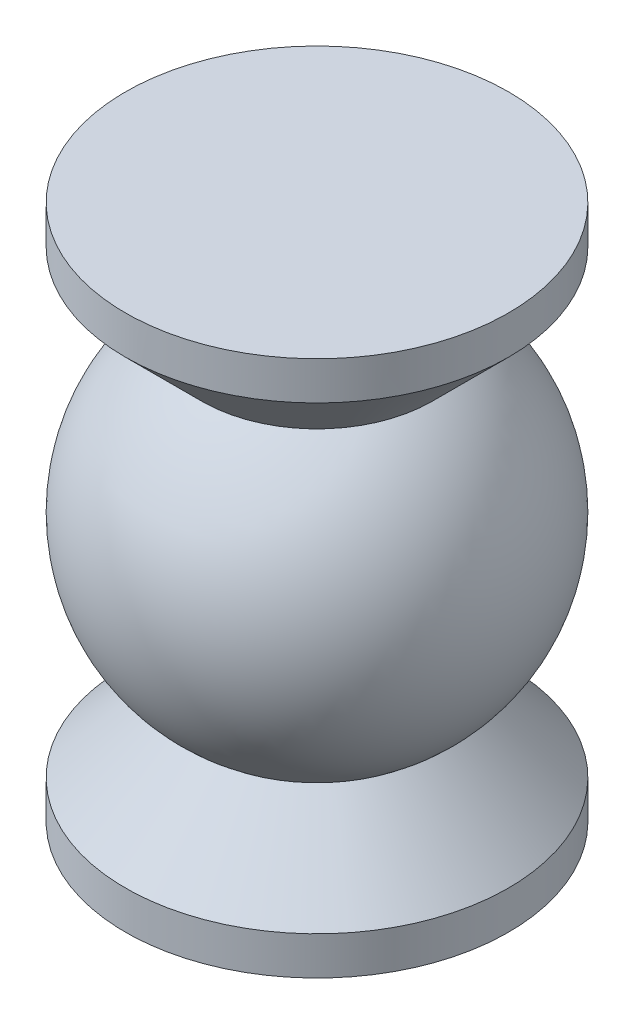
SolidWorks part; units mm, degrees
ref_plane "前视基准面" through (0, 0, 0) normal (0, 0, 1) x (1, 0, 0)
ref_plane "上视基准面" through (0, 0, 0) normal (0, 1, 0) x (1, 0, 0)
ref_plane "右视基准面" through (0, 0, 0) normal (1, 0, 0) x (0, 0, -1)
sketch "草图1" plane through (0, 0, 0) normal (0, 0, 1) x (1, 0, 0)
  line L0 (0, 0) -> (0, 23.8608) construction
  line L1 (0, 0) -> (25, 0)
  line L2 (25, 0) -> (25, 5)
  line L3 (25, 5) -> (15, 15)
  line L4 (15, 55) -> (25, 65)
  line L5 (25, 65) -> (25, 70)
  line L6 (25, 70) -> (0, 70)
  line L7 (0, 0) -> (0, 70)
  arc A0 (15, 15) -> (15, 55) centre (0, 35) ccw
  point P8 (0, 0)
  point P11 (12.1221, 55.7721)
  point P13 (0, 0)
  point P14 (0, 0)
  point P15 (15, 55.2738)
  point P16 (31.159, 65)
  dimension "D1" = 5
  dimension "D5" = 25
  dimension "D2" = 5
  dimension "D3" = 40
  dimension "D4" = 70
  dimension "D6" = 35
  dimension "D7" = 25
revolve "旋转1" add sketch "草图1" angle 360 about L0
